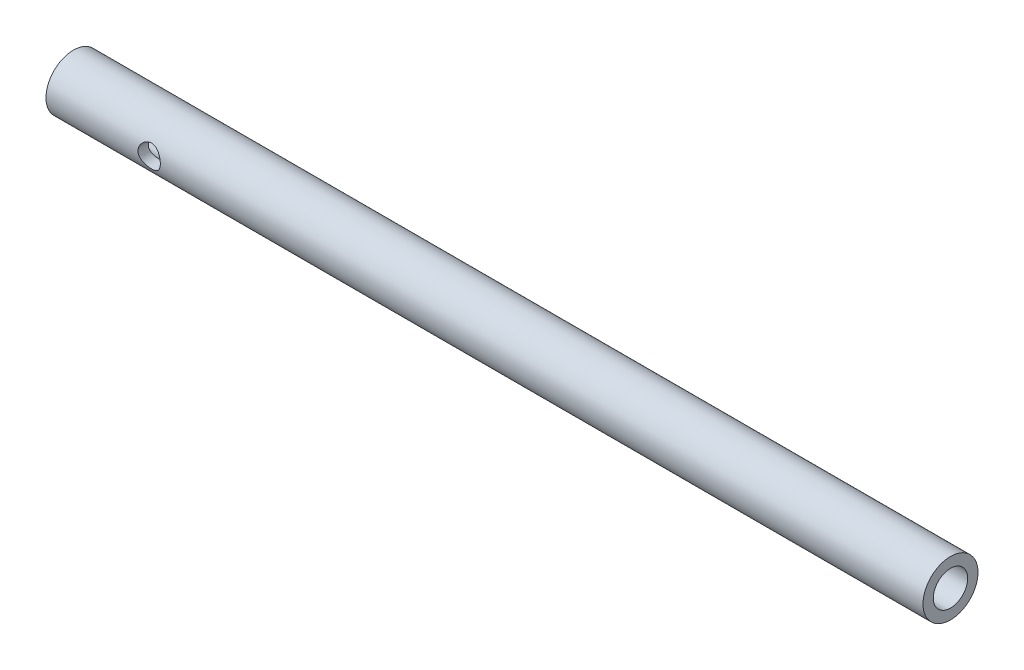
SolidWorks part; units mm, degrees
ref_plane "Front Plane" through (0, 0, 0) normal (0, 0, 1) x (1, 0, 0)
ref_plane "Top Plane" through (0, 0, 0) normal (0, 1, 0) x (1, 0, 0)
ref_plane "Right Plane" through (0, 0, 0) normal (1, 0, 0) x (0, 0, -1)
sketch "Sketch1" plane through (0, 0, 0) normal (1, 0, 0) x (0, 0, -1)
  circle A0 centre (0, 0) radius 16
  circle A1 centre (0, 0) radius 10
  dimension "D1" = 32
  dimension "D2" = 20
extrude "Boss-Extrude1" add sketch "Sketch1" against normal blind 510
sketch "Sketch2" plane through (0, 0, 0) normal (0, 0, 1) x (1, 0, 0)
  line L0 (-510, 16) -> (-510, -16) construction
  line L1 (-510, 0) -> (-604.8317, 0) construction
  circle A0 centre (-450, 0) radius 6.5
  dimension "D1" = 13
  dimension "D2" = 60
extrude "Cut-Extrude1" cut sketch "Sketch2" against normal mid plane 59
